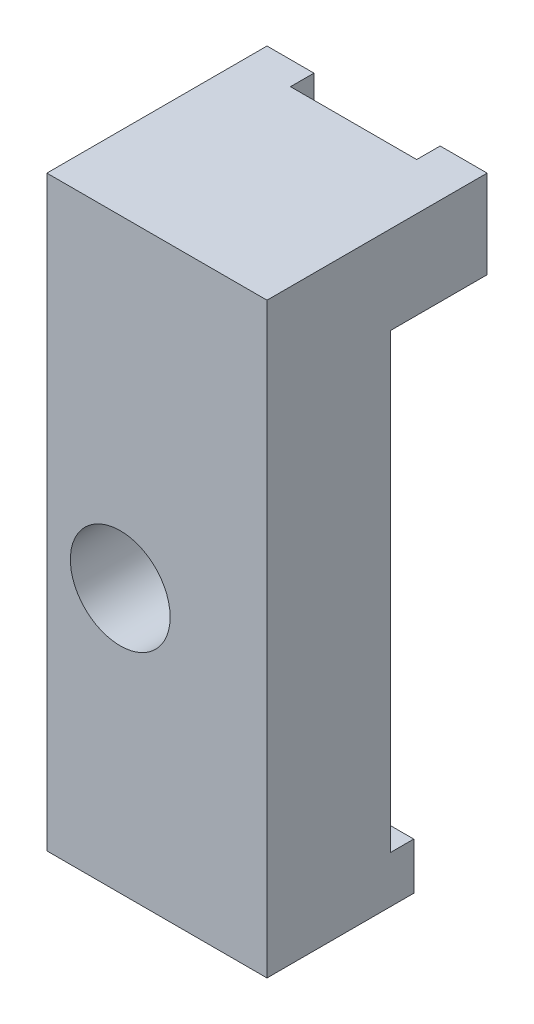
SolidWorks part; units mm, degrees
ref_plane "Front Plane" through (0, 0, 0) normal (0, 0, 1) x (1, 0, 0)
ref_plane "Top Plane" through (0, 0, 0) normal (0, 1, 0) x (1, 0, 0)
ref_plane "Right Plane" through (0, 0, 0) normal (1, 0, 0) x (0, 0, -1)
sketch "Sketch1" plane through (0, 0, 0) normal (0, 0, 1) x (1, 0, 0)
  line L1 (-4.7625, 12.7) -> (4.7625, 12.7)
  line L2 (-4.7625, 12.7) -> (-4.7625, -12.7)
  line L3 (-4.7625, -12.7) -> (4.7625, -12.7)
  line L4 (4.7625, 12.7) -> (4.7625, -12.7)
  line L5 (-4.7625, 12.7) -> (4.7625, -12.7) construction
  line L6 (-4.7625, -12.7) -> (4.7625, 12.7) construction
  point P0 (0, 0)
  dimension "D1" = 25.4
  dimension "D2" = 9.525
extrude "Boss-Extrude1" add sketch "Sketch1" along normal mid plane 9.525
sketch "Sketch2" plane through (4.7625, 0, 0) normal (1, 0, 0) x (0, 0, -1)
  line L0 (-4.7625, -12.7) -> (-4.7625, 12.7) construction
  line L1 (4.7625, -12.7) -> (1.5875, -12.7)
  line L2 (4.7625, -12.7) -> (4.7625, 8.89)
  line L3 (4.7625, 8.89) -> (1.5875, 8.89)
  line L4 (1.5875, -12.7) -> (1.5875, 8.89)
  line L5 (-4.7625, 12.7) -> (4.7625, 12.7) construction
  dimension "D1" = 6.35
  dimension "D2" = 3.81
extrude "Cut-Extrude1" cut sketch "Sketch2" against normal up to next
sketch "Sketch3" plane through (0, 0, 4.7625) normal (0, 0, 1) x (1, 0, 0)
  line L0 (-4.7625, -12.7) -> (4.7625, -12.7) construction
  line L1 (-4.7625, 12.7) -> (-4.7625, -12.7) construction
  circle A0 centre (-1.5875, -1.27) radius 2.159
  dimension "D1" = 11.43
  dimension "D2" = 3.175
extrude "Cut-Extrude2" cut sketch "Sketch3" against normal up to next
sketch "Sketch4" plane through (0, 12.7, 0) normal (0, 1, 0) x (1, 0, 0)
  line L0 (4.7625, 4.7625) -> (-4.7625, 4.7625) construction
  line L1 (2.7305, 4.7625) -> (-2.7305, 4.7625)
  line L2 (2.7305, 4.7625) -> (2.7305, 3.7465)
  line L3 (2.7305, 3.7465) -> (-2.7305, 3.7465)
  line L4 (-2.7305, 4.7625) -> (-2.7305, 3.7465)
  line L5 (-4.7625, -4.7625) -> (-4.7625, 4.7625) construction
  line L6 (4.7625, -4.7625) -> (4.7625, 4.7625) construction
  dimension "D1" = 2.032
  dimension "D2" = 2.032
  dimension "D3" = 1.016
extrude "Cut-Extrude3" cut sketch "Sketch4" against normal up to next
sketch "Sketch5" plane through (4.7625, 0, 0) normal (1, 0, 0) x (0, 0, -1)
  line L0 (1.5875, 8.89) -> (1.5875, -12.7) construction
  line L1 (1.5875, -10.668) -> (0.5715, -10.668)
  line L2 (1.5875, -10.668) -> (1.5875, 8.89)
  line L3 (1.5875, 8.89) -> (0.5715, 8.89)
  line L4 (0.5715, -10.668) -> (0.5715, 8.89)
  line L5 (-4.7625, -12.7) -> (1.5875, -12.7) construction
  line L6 (4.7625, 8.89) -> (1.5875, 8.89) construction
  dimension "D1" = 2.032
  dimension "D2" = 1.016
extrude "Cut-Extrude4" cut sketch "Sketch5" against normal through all
